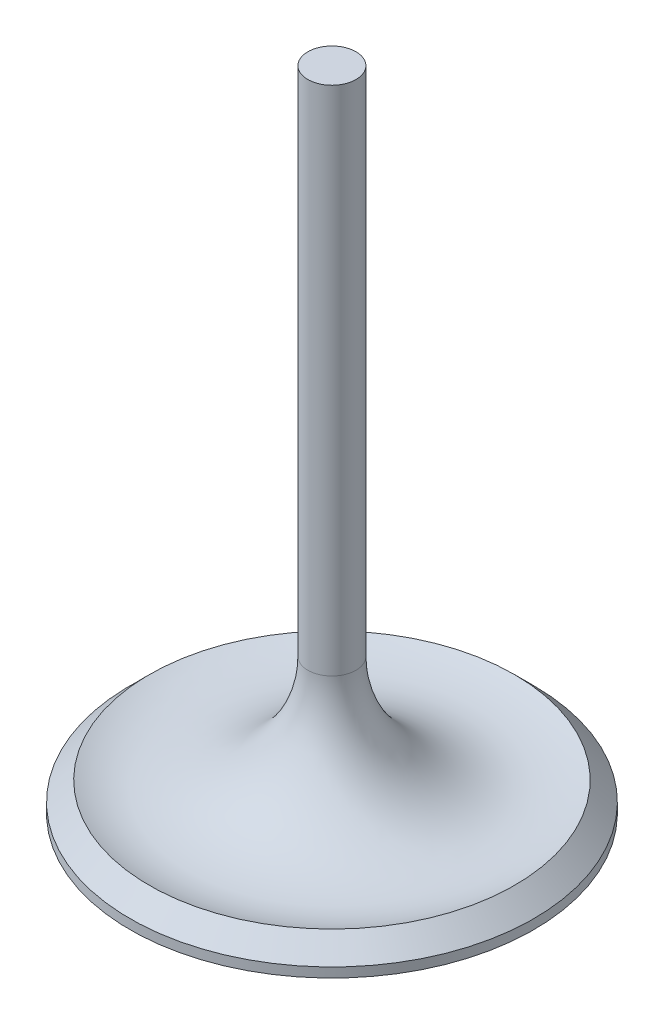
SolidWorks part; units mm, degrees
ref_plane "Front Plane" through (0, 0, 0) normal (0, 0, 1) x (1, 0, 0)
ref_plane "Top Plane" through (0, 0, 0) normal (0, 1, 0) x (1, 0, 0)
ref_plane "Right Plane" through (0, 0, 0) normal (1, 0, 0) x (0, 0, -1)
sketch "Sketch1" plane through (0, 0, 0) normal (0, 0, 1) x (1, 0, 0)
  line L0 (0, 0) -> (0, 85.55)
  line L1 (0, 85.55) -> (3.18, 85.55)
  line L2 (3.18, 85.55) -> (3.18, 17.9547)
  line L3 (24.13, 3.81) -> (26.67, 1.27)
  line L4 (26.67, 1.27) -> (26.67, 0)
  line L5 (26.67, 0) -> (0, 0)
  arc A0 (3.18, 17.9547) -> (24.13, 3.81) centre (18.43, 17.9547) ccw
  dimension "D7" = 15.25
  dimension "D1" = 85.55
  dimension "D2" = 26.67
  dimension "D3" = 3.18
  dimension "D4" = 1.27
  dimension "D5" = 3.81
  dimension "D6" = 45
revolve "Revolve1" add sketch "Sketch1" angle 360 about L0
